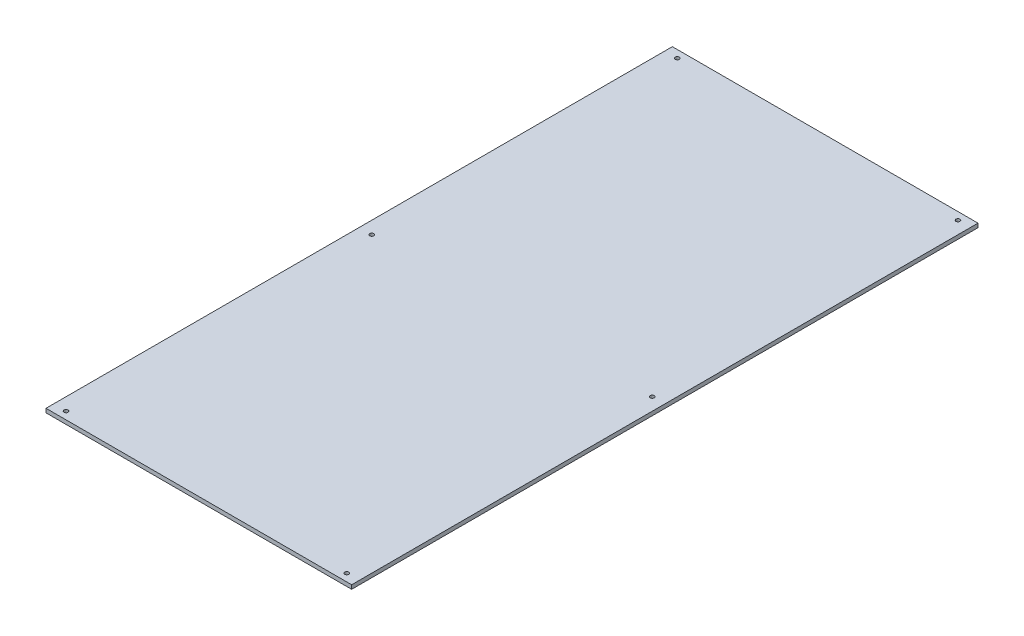
SolidWorks part; units mm, degrees
ref_plane "Front Plane" through (0, 0, 0) normal (0, 0, 1) x (1, 0, 0)
ref_plane "Top Plane" through (0, 0, 0) normal (0, 1, 0) x (1, 0, 0)
ref_plane "Right Plane" through (0, 0, 0) normal (1, 0, 0) x (0, 0, -1)
sketch "Sketch1" plane through (0, 0, 0) normal (0, 1, 0) x (1, 0, 0)
  line L0 (-122, 0) -> (122, 0) construction
  line L1 (-122, -250) -> (122, -250)
  line L2 (-122, -250) -> (-122, 250)
  line L3 (-122, 250) -> (122, 250)
  line L4 (122, -250) -> (122, 250)
  line L5 (-122, -250) -> (122, 250) construction
  line L6 (-122, 250) -> (122, -250) construction
  line L7 (0, 250) -> (0, -250) construction
  circle A0 centre (112, 244) radius 1.6
  circle A1 centre (112, 0) radius 1.6
  circle A2 centre (112, -244) radius 1.6
  circle A3 centre (-112, -244) radius 1.6
  circle A4 centre (-112, 0) radius 1.6
  circle A5 centre (-112, 244) radius 1.6
  point P0 (0, 0)
  dimension "D5" = 3.2
  dimension "D7" = 3.2
  dimension "D1" = 500
  dimension "D2" = 244
  dimension "D3" = 10
  dimension "D4" = 244
  dimension "D6" = 10
extrude "Boss-Extrude1" add sketch "Sketch1" along normal blind 3.175
